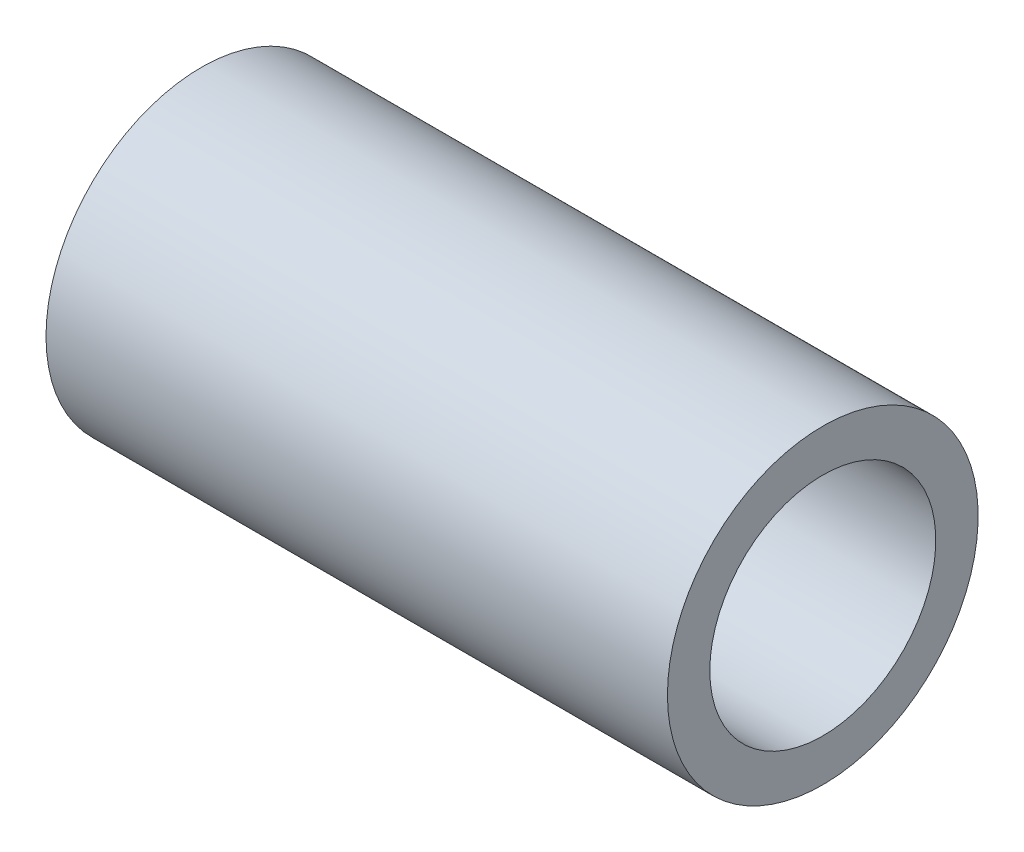
SolidWorks part; units mm, degrees
material "Latão com alto teor de chumbo, UNS C34200"
ref_plane "Plano frontal" through (0, 0, 0) normal (0, 0, 1) x (1, 0, 0)
ref_plane "Plano superior" through (0, 0, 0) normal (0, 1, 0) x (1, 0, 0)
ref_plane "Plano direito" through (0, 0, 0) normal (1, 0, 0) x (0, 0, -1)
sketch "Esboço1" plane through (0, 0, 0) normal (0, 0, 1) x (1, 0, 0)
  line L0 (0, 0) -> (22, 0) construction
  line L2 (0, 4) -> (22, 4)
  line L3 (0, 4) -> (0, 5.5)
  line L4 (0, 5.5) -> (22, 5.5)
  line L5 (22, 4) -> (22, 5.5)
  dimension "D1" = 22
  dimension "D2" = 4
  dimension "D3" = 5.5
revolve "Corpo - Furo Ø8x22" add sketch "Esboço1" angle 360 about L0
